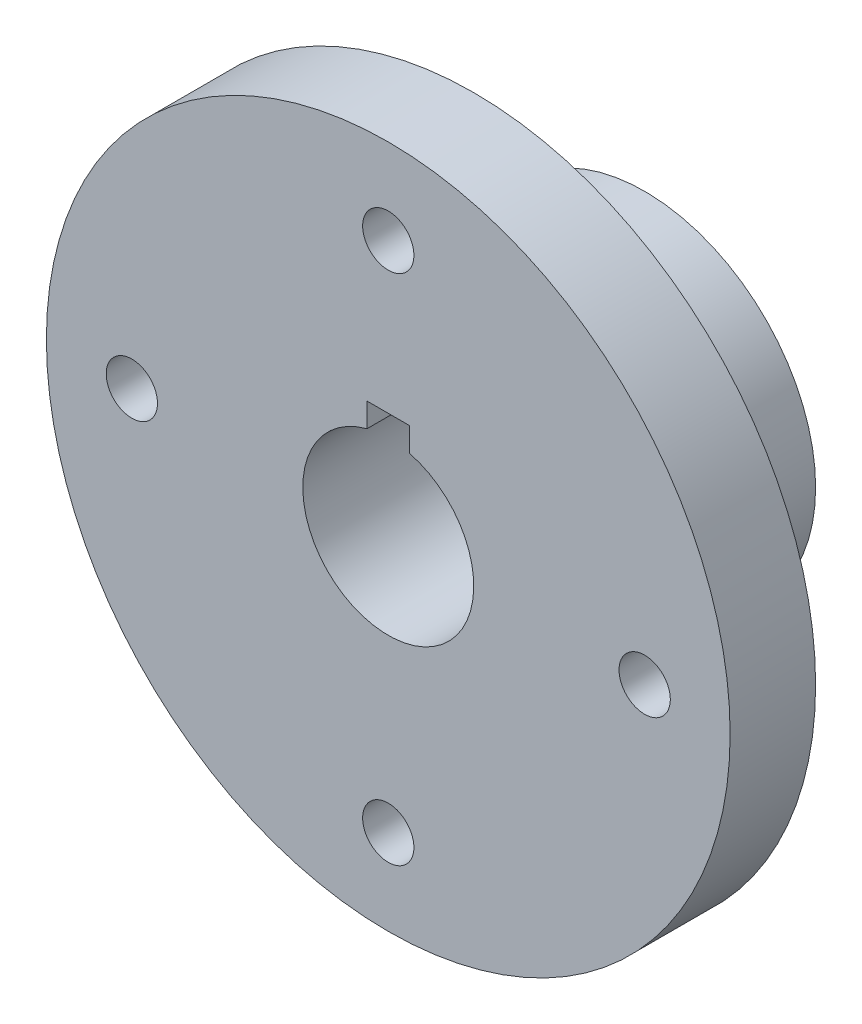
SolidWorks part; units mm, degrees
ref_plane "Front Plane" through (0, 0, 0) normal (0, 0, 1) x (1, 0, 0)
ref_plane "Top Plane" through (0, 0, 0) normal (0, 1, 0) x (1, 0, 0)
ref_plane "Right Plane" through (0, 0, 0) normal (1, 0, 0) x (0, 0, -1)
sketch "Sketch1" plane through (0, 0, 0) normal (0, 0, 1) x (1, 0, 0)
  circle A0 centre (0, 0) radius 200
extrude "Boss-Extrude1" add sketch "Sketch1" along normal blind 50
sketch "Sketch3" plane through (0, 0, 0) normal (0, 0, -1) x (-1, 0, 0)
  circle A0 centre (0, 0) radius 100
extrude "Boss-Extrude2" add sketch "Sketch3" along normal blind 100
sketch "Sketch4" plane through (0, 0, 50) normal (0, 0, 1) x (1, 0, 0)
  circle A0 centre (0, 150) radius 15
  circle A1 centre (150, 0) radius 15
  circle A2 centre (0, -150) radius 15
  circle A3 centre (-150, 0) radius 15
  point P12 (0, 0)
  dimension "D1" = 150
  dimension "D2" = 4
extrude "Cut-Extrude1" cut sketch "Sketch4" against normal blind 100
sketch "Sketch5" plane through (0, 0, 50) normal (0, 0, 1) x (1, 0, 0)
  circle A0 centre (0, 0) radius 50
extrude "Cut-Extrude2" cut sketch "Sketch5" against normal through all
sketch "Sketch6" plane through (0, 0, 50) normal (0, 0, 1) x (1, 0, 0)
  line L1 (-12.5, 62.5) -> (12.5, 62.5)
  line L2 (-12.5, 62.5) -> (-12.5, 37.5)
  line L3 (-12.5, 37.5) -> (12.5, 37.5)
  line L4 (12.5, 62.5) -> (12.5, 37.5)
  line L5 (-12.5, 62.5) -> (12.5, 37.5) construction
  line L6 (-12.5, 37.5) -> (12.5, 62.5) construction
  circle A0 centre (0, 0) radius 50 construction
  point P0 (0, 50)
extrude "Cut-Extrude3" cut sketch "Sketch6" against normal through all
